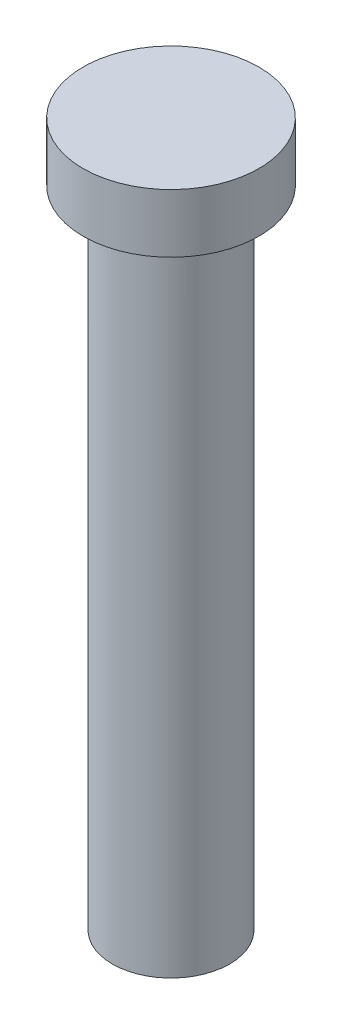
SolidWorks part; units mm, degrees
ref_plane "Front Plane" through (0, 0, 0) normal (0, 0, 1) x (1, 0, 0)
ref_plane "Top Plane" through (0, 0, 0) normal (0, 1, 0) x (1, 0, 0)
ref_plane "Right Plane" through (0, 0, 0) normal (1, 0, 0) x (0, 0, -1)
sketch "Sketch1" plane through (0, 0, 0) normal (0, 1, 0) x (1, 0, 0)
  circle A1 centre (0, 0) radius 4.7625
  dimension "D2" = 9.525
extrude "Boss-Extrude1" add sketch "Sketch1" along normal blind 3.175
sketch "Sketch2" plane through (0, 0, 0) normal (0, -1, 0) x (1, 0, 0)
  circle A0 centre (0, 0) radius 3.175
  dimension "D1" = 6.35
extrude "Boss-Extrude2" add sketch "Sketch2" along normal blind 34.925
